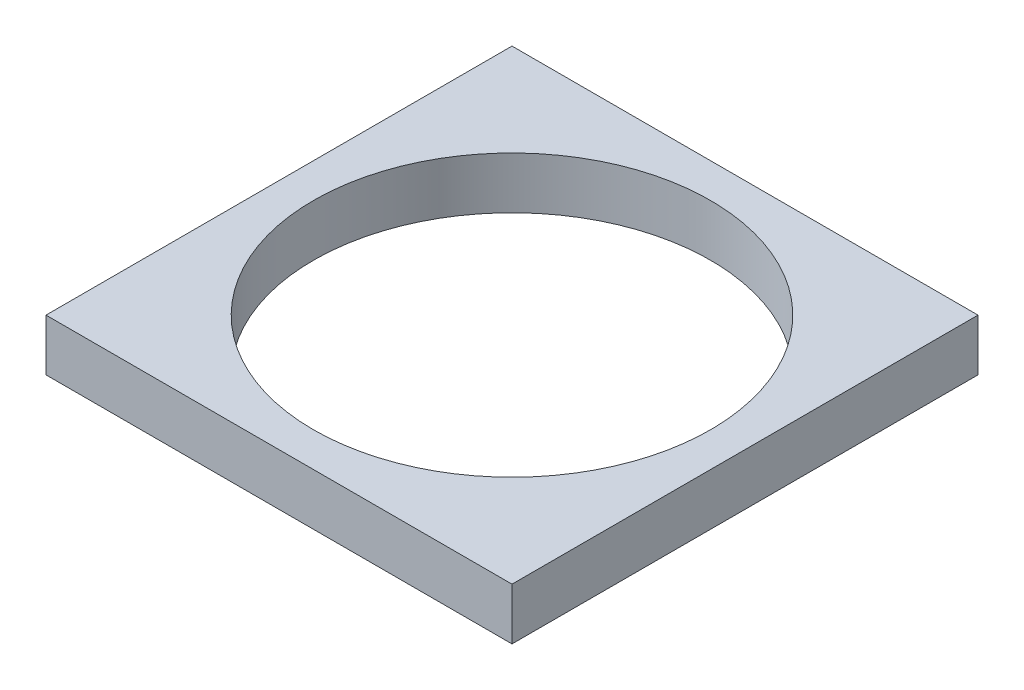
SolidWorks part; units mm, degrees
ref_plane "Front Plane" through (0, 0, 0) normal (0, 0, 1) x (1, 0, 0)
ref_plane "Top Plane" through (0, 0, 0) normal (0, 1, 0) x (1, 0, 0)
ref_plane "Right Plane" through (0, 0, 0) normal (1, 0, 0) x (0, 0, -1)
sketch "Sketch1" plane through (0, 0, 0) normal (0, 1, 0) x (1, 0, 0)
  line L1 (-22.5, -22.5) -> (22.5, -22.5)
  line L2 (-22.5, -22.5) -> (-22.5, 22.5)
  line L3 (-22.5, 22.5) -> (22.5, 22.5)
  line L4 (22.5, -22.5) -> (22.5, 22.5)
  line L5 (-22.5, -22.5) -> (22.5, 22.5) construction
  line L6 (-22.5, 22.5) -> (22.5, -22.5) construction
  circle A0 centre (0, 0) radius 19.375 construction
  dimension "D1" = 38.75
  dimension "D2" = 45
extrude "Boss-Extrude1" add sketch "Sketch1" along normal blind 5
sketch "Sketch2" plane through (0, 5, 0) normal (0, 1, 0) x (1, 0, 0)
  circle A0 centre (0, 0) radius 19.175
  dimension "D1" = 38.35
extrude "Cut-Extrude1" cut sketch "Sketch2" against normal blind 5
